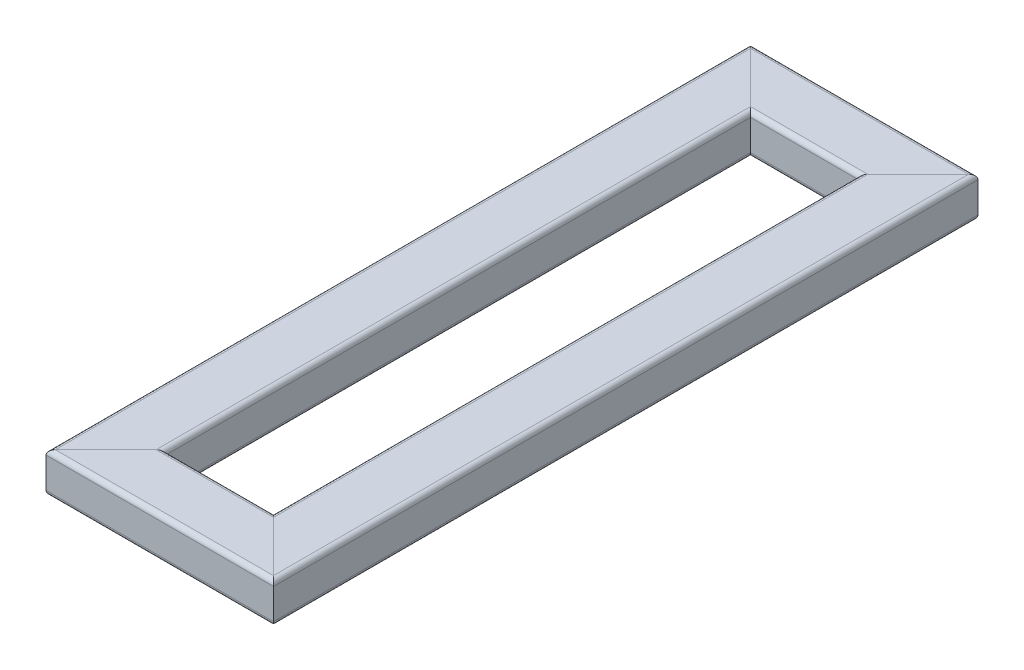
SolidWorks part; units mm, degrees
material "ASTM A36 Acero"
ref_plane "Alzado" through (0, 0, 0) normal (0, 0, 1) x (1, 0, 0)
ref_plane "Planta" through (0, 0, 0) normal (0, 1, 0) x (1, 0, 0)
ref_plane "Vista lateral" through (0, 0, 0) normal (1, 0, 0) x (0, 0, -1)
sketch "Croquis1" plane through (0, 0, 0) normal (0, 1, 0) x (1, 0, 0)
  line L1 (-145, 449) -> (145, 449)
  line L2 (-145, 449) -> (-145, -449)
  line L3 (-145, -449) -> (145, -449)
  line L4 (145, 449) -> (145, -449)
  line L5 (-145, 449) -> (145, -449) construction
  line L6 (-145, -449) -> (145, 449) construction
  point P0 (0, 0)
  dimension "D1" = 898
  dimension "D2" = 290
other "Tubo rectangular 3 X 2 X 0.25(1)"
ref_plane "Plano1" through (-106.9, 25.4, -449) normal (0, 0, 1) x (1, 0, 0)
sketch "Sketch1" plane through (-106.9, 25.4, -449) normal (0, 0, 1) x (1, 0, 0)
  line L0 (-32.1, -22.4) -> (32.1, -22.4)
  line L1 (-35.1, -19.4) -> (-35.1, 19.4)
  line L2 (32.1, 22.4) -> (-32.1, 22.4)
  line L3 (35.1, 19.4) -> (35.1, -19.4)
  line L4 (-32.1, -25.4) -> (32.1, -25.4)
  line L5 (-38.1, -19.4) -> (-38.1, 19.4)
  line L6 (32.1, 25.4) -> (-32.1, 25.4)
  line L7 (38.1, 19.4) -> (38.1, -19.4)
  line L8 (0, 0) -> (38.1, 0) construction
  line L9 (0, 0) -> (0, 25.4) construction
  arc A0 (38.1, 19.4) -> (32.1, 25.4) centre (32.1, 19.4) ccw
  arc A1 (32.1, -25.4) -> (38.1, -19.4) centre (32.1, -19.4) ccw
  arc A2 (-38.1, -19.4) -> (-32.1, -25.4) centre (-32.1, -19.4) ccw
  arc A3 (-32.1, 25.4) -> (-38.1, 19.4) centre (-32.1, 19.4) ccw
  arc A4 (-32.1, 22.4) -> (-35.1, 19.4) centre (-32.1, 19.4) ccw
  arc A5 (35.1, 19.4) -> (32.1, 22.4) centre (32.1, 19.4) ccw
  arc A6 (32.1, -22.4) -> (35.1, -19.4) centre (32.1, -19.4) ccw
  arc A7 (-35.1, -19.4) -> (-32.1, -22.4) centre (-32.1, -19.4) ccw
  point P3 (0, -25.4)
  point P4 (-38.1, 0)
  point P5 (0, 0)
  point P6 (38.1, -25.4)
  point P7 (-38.1, -25.4)
  point P8 (-38.1, 25.4)
  point P33 (0, 0)
  point P35 (38.1, 25.4)
  point P36 (38.1, 0)
  point P37 (0, 25.4)
  dimension "D1" = 6
  dimension "Thickness" = 3
  dimension "V_leg" = 50.8
  dimension "H_leg" = 76.2
